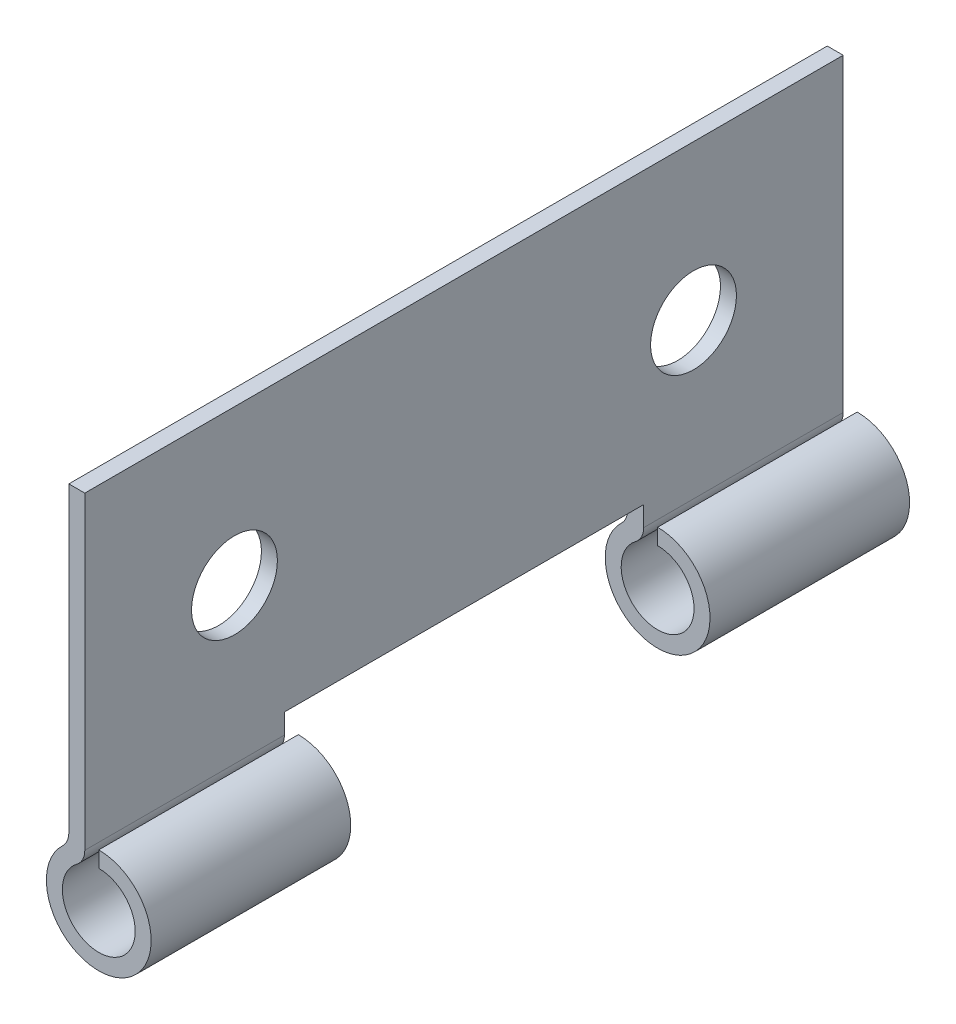
SolidWorks part; units mm, degrees
ref_plane "Front Plane" through (0, 0, 0) normal (0, 0, 1) x (1, 0, 0)
ref_plane "Top Plane" through (0, 0, 0) normal (0, 1, 0) x (1, 0, 0)
ref_plane "Right Plane" through (0, 0, 0) normal (1, 0, 0) x (0, 0, -1)
sketch "Sketch1" plane through (0, 0, 0) normal (0, 0, 1) x (1, 0, 0)
  line L1 (0.8, -0.3688) -> (0.8, 15.1312)
  line L2 (0, 0) -> (0, 15.1312)
  line L3 (0, 15.1312) -> (0.8, 15.1312)
  line L4 (0, 0) -> (1.5, 0) construction
  line L5 (1.5, 0) -> (1.5, -2.625) construction
  line L6 (1.5, 0) -> (1.5, -0.8)
  arc A0 (-0.3103, -0.7241) -> (1.5, 0) centre (1.5, -2.625) ccw
  arc A1 (0.4018, -1.1674) -> (1.5, -0.8) centre (1.5, -2.625) ccw
  arc A2 (0, 0) -> (-0.3103, -0.7241) centre (-1, 0) cw
  circle A3 centre (1.5, -2.625) radius 2.625 construction
  circle A4 centre (1.5, -2.625) radius 1.825 construction
  arc A5 (0.4018, -1.1674) -> (0.8, -0.3688) centre (-0.2, -0.3688) ccw
  point P7 (3.325, -2.625)
  point P15 (4.0103, -1.8575)
  dimension "D2" = 1
  dimension "D3" = 1
  dimension "D1" = 0.8
extrude "Boss-Extrude1" add sketch "Sketch1" along normal blind 38
sketch "Sketch2" plane through (0.8, 0, 0) normal (1, 0, 0) x (0, 0, -1)
  line L0 (-38, 7.3812) -> (0, 7.3812) construction
  line L1 (-38, -0.3688) -> (-38, 15.1312) construction
  line L2 (0, -0.3688) -> (0, 15.1312) construction
  line L3 (-30.5, 9.5312) -> (-0.6946, 9.5312) construction
  circle A0 centre (-30.5, 7.3812) radius 2.15
  circle A1 centre (-7.5, 7.3812) radius 2.15
  dimension "D1" = 4.3
  dimension "D3" = 7.5
  dimension "D2" = 7.5
extrude "Cut-Extrude1" cut sketch "Sketch2" against normal up to next
sketch "Sketch3" plane through (0.8, 0, 0) normal (1, 0, 0) x (0, 0, -1)
  line L0 (-19, 15.1312) -> (-19, 0.6312) construction
  line L1 (-38, 15.1312) -> (0, 15.1312) construction
  line L3 (-28, 0.6312) -> (-10, 0.6312)
  line L6 (-28, 0.6312) -> (-28, -5.25)
  line L8 (-28, 0.6312) -> (-28, -5.25)
  line L10 (-10, 0.6312) -> (-10, -5.25)
  line L11 (-28, -5.25) -> (-10, -5.25)
  line L12 (-10, 0.6312) -> (-10, -5.25)
  line M7 (-38, -0.3688) -> (0, -0.3688)
extrude "Cut-Extrude4" cut sketch "Sketch3" against normal through all both and the other way through all contours L10 L3 L6 M7 | L6 L11 L10 M7
